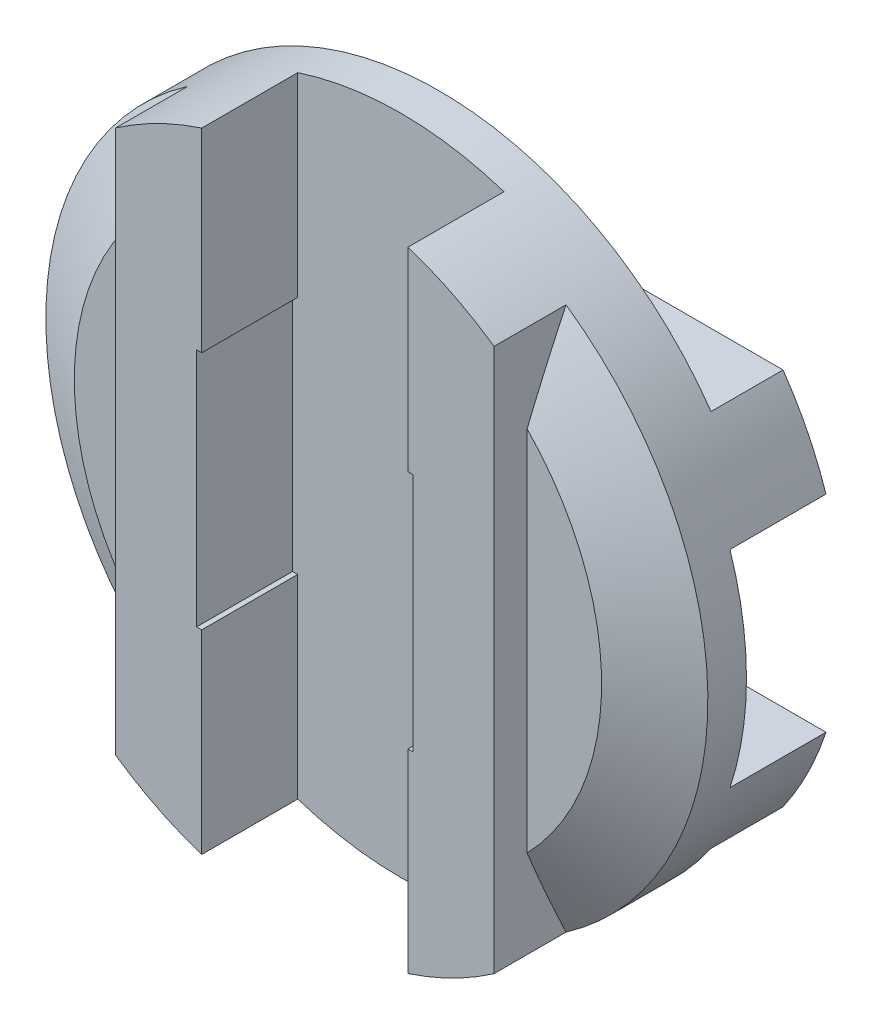
SolidWorks part; units mm, degrees
ref_plane "Front" through (0, 0, 0) normal (0, 0, 1) x (1, 0, 0)
ref_plane "Top" through (0, 0, 0) normal (0, 1, 0) x (1, 0, 0)
ref_plane "Right" through (0, 0, 0) normal (1, 0, 0) x (0, 0, -1)
sketch "Sketch1" plane through (0, 0, 0) normal (0, 0, 1) x (1, 0, 0)
  circle A0 centre (0, 0) radius 12.7
  point P3 (0, 12.7)
extrude "Boss-Extrude1" add sketch "Sketch1" against normal mid plane 7.9248
sketch "Sketch2" plane through (0, 0, 3.9624) normal (0, 0, 1) x (1, 0, 0)
  line L0 (-3.956, 12.7) -> (3.9561, -12.7) construction
  line L1 (-3.956, 12.7) -> (3.9561, 12.7)
  line L2 (-3.956, 12.7) -> (-3.956, -12.7)
  line L3 (-3.956, -12.7) -> (3.9561, -12.7)
  line L4 (3.9561, 12.7) -> (3.9561, -12.7)
  circle A0 centre (0, 0) radius 12.7 construction
extrude "Cut-Extrude1" cut sketch "Sketch2" against normal blind 3.683
sketch "Sketch3" plane through (0, 0, -3.9624) normal (0, 0, -1) x (-1, 0, 0)
  line L1 (-12.7, 3.9561) -> (12.7, 3.9561)
  line L2 (-12.7, 3.9561) -> (-12.7, -3.956)
  line L3 (-12.7, -3.956) -> (12.7, -3.956)
  line L4 (12.7, 3.9561) -> (12.7, -3.956)
  line L14 (3.956, 12.7) -> (-3.9561, 12.7) construction
  line L15 (12.7, 3.9561) -> (-12.7, -3.956) construction
  circle A0 centre (0, 0) radius 12.7 construction
extrude "Cut-Extrude2" cut sketch "Sketch3" against normal blind 3.683
sketch "Sketch4" plane through (0, 0, 3.9624) normal (0, 0, 1) x (1, 0, 0)
  line L0 (-3.956, 0) -> (-7.2581, 0) construction
  line L1 (12.7, 12.7) -> (7.2581, 12.7)
  line L2 (12.7, 12.7) -> (12.7, -12.7)
  line L3 (12.7, -12.7) -> (7.2581, -12.7)
  line L4 (7.2581, 12.7) -> (7.2581, -12.7)
  line L5 (-12.7, 12.7) -> (-7.2581, 12.7)
  line L6 (-12.7, 12.7) -> (-12.7, -12.7)
  line L7 (-12.7, -12.7) -> (-7.258, -12.7)
  line L8 (-7.2581, 12.7) -> (-7.258, -12.7)
  line L9 (-3.956, 12.0681) -> (-3.956, -12.0681) construction
  line L10 (3.956, 0) -> (7.2581, 0) construction
  line L11 (3.9561, -12.0681) -> (3.9561, 12.0681) construction
  line L12 (-3.956, 12.7) -> (3.9561, 12.7) construction
  line L13 (-3.956, -12.7) -> (3.9561, -12.7) construction
  line L14 (3.9561, 12.7) -> (3.9561, -12.7) construction
  circle A1 centre (0, 0) radius 12.7 construction
extrude "Cut-Extrude3" cut sketch "Sketch4" against normal blind 1.27
sketch "Sketch5" plane through (0, 0, -3.9624) normal (0, 0, -1) x (-1, 0, 0)
  line L0 (-12.7, 12.7) -> (-7.2581, 12.7) construction
  line L1 (-12.7, 12.7) -> (12.7, 12.7)
  line L2 (-12.7, 12.7) -> (-12.7, 7.258)
  line L3 (-12.7, 7.258) -> (12.7, 7.258)
  line L4 (12.7, 12.7) -> (12.7, 7.258)
  line L5 (12.7, -12.7) -> (-12.7, -12.7)
  line L6 (12.7, -12.7) -> (12.7, -7.258)
  line L7 (12.7, -7.258) -> (-12.7, -7.258)
  line L8 (-12.7, -12.7) -> (-12.7, -7.258)
  line L9 (0, 3.9561) -> (0, 7.258) construction
  line L10 (-12.0681, 3.9561) -> (12.0681, 3.9561) construction
  line L11 (-12.7, 3.9561) -> (-12.7, -3.956) construction
  line L12 (0, -7.258) -> (0, -3.956) construction
  line L13 (-12.0681, -3.956) -> (12.0681, -3.956) construction
  circle A0 centre (0, 0) radius 12.7 construction
extrude "Cut-Extrude4" cut sketch "Sketch5" against normal blind 1.27
chamfer "Chamfer1" distance 2.5849 angle 30 4 edges at (0, -12.7, -2.6924) (0, 12.7, -2.6924) (-12.7, 0, 2.6924) (12.7, 0, 2.6924)
sketch "Sketch6" plane through (0, 0, 3.9624) normal (0, 0, 1) x (1, 0, 0)
  line L0 (-4.1539, 4.6037) -> (4.1539, -4.6037) construction
  line L1 (-4.1539, 4.6037) -> (4.1539, 4.6037)
  line L2 (-4.1539, 4.6037) -> (-4.1539, -4.6037)
  line L3 (-4.1539, -4.6037) -> (4.1539, -4.6037)
  line L4 (4.1539, 4.6037) -> (4.1539, -4.6037)
  dimension "D1" = 8.3077
  dimension "D2" = 9.2075
extrude "Cut-Extrude5" cut sketch "Sketch6" against normal up to surface (3.683 mm away) up to face at (0, 0, 0.2794)
sketch "Sketch7" plane through (0, 0, -3.9624) normal (0, 0, -1) x (-1, 0, 0)
  line L0 (-4.6037, 4.1539) -> (4.6037, -4.1539) construction
  line L1 (-4.6037, 4.1539) -> (4.6037, 4.1539)
  line L2 (-4.6037, 4.1539) -> (-4.6037, -4.1539)
  line L3 (-4.6037, -4.1539) -> (4.6037, -4.1539)
  line L4 (4.6037, 4.1539) -> (4.6037, -4.1539)
  line L5 (4.1539, 4.6037) -> (4.1539, -4.6037) construction
  line L6 (4.1539, 4.6037) -> (-4.1539, 4.6037) construction
extrude "Cut-Extrude6" cut sketch "Sketch7" against normal up to surface (3.683 mm away) up to face at (0, 0, -0.2794)
sketch "Sketch8" plane through (0, 0, 0) normal (1, 0, 0) x (0, 0, -1)
  line L0 (-3.9624, 12.0681) -> (-3.9624, 4.6037) construction
  line L2 (3.9624, 3.9561) -> (3.9624, 7.258) construction
  point P0 (3.9624, 12.7)
  point P1 (-3.9624, 12.7)
equation "\"D1@Cut-Extrude2\" = \"Tooth depth@Cut-Extrude1\""
equation "\"D1@Cut-Extrude4\" = \"Tooth depth 2@Cut-Extrude3\""
equation "\"D1@Chamfer1\" = \"D1@Sketch4\" * .475"
equation "\"D1@Sketch6\" = \"Tooth gap@Sketch2\" * 1.05"
equation "\"D2@Sketch6\" = \"OD@Sketch1\" * .3625"
